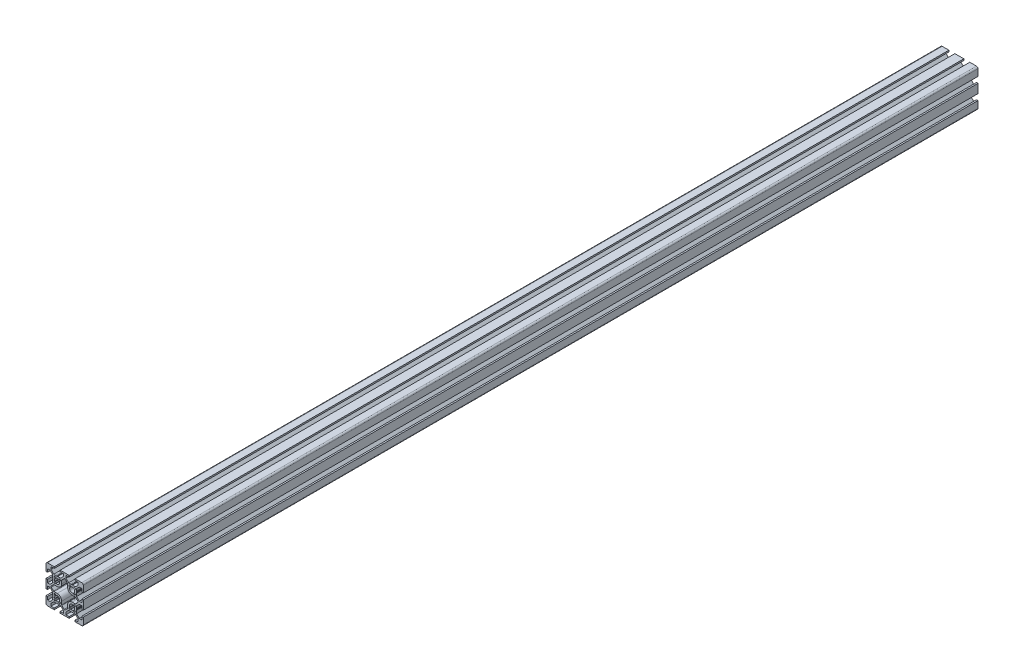
SolidWorks part; units mm, degrees
ref_plane "Front Plane" through (0, 0, 0) normal (0, 0, 1) x (1, 0, 0)
ref_plane "Top Plane" through (0, 0, 0) normal (0, 1, 0) x (1, 0, 0)
ref_plane "Right Plane" through (0, 0, 0) normal (1, 0, 0) x (0, 0, -1)
ref_plane "Plane1" through (0, 0, 0) normal (0, 0, 1) x (1, 0, 0)
sketch "Sketch1" plane through (0, 0, 0) normal (0, 0, 1) x (1, 0, 0)
  line L0 (-25, 23) -> (-25, 14)
  line L1 (-25, 14) -> (-23, 14)
  line L2 (-23, 14) -> (-23, 18.25)
  line L3 (-23, 18.25) -> (-19.6642, 18.25)
  line L4 (-19.6642, 18.25) -> (-16, 14.5858)
  line L5 (-16, 14.5858) -> (-16, 10.6536)
  line L6 (-15.933, 10.4036) -> (-15.7, 10)
  line L7 (-15.7, 10) -> (-15.933, 9.5964)
  line L8 (-15.933, 9.0964) -> (-15.751, 8.7811)
  line L9 (-15.751, 8.7811) -> (-16, 7.5)
  line L10 (-16, 7.5) -> (-16, 5.4142)
  line L11 (-16, 5.4142) -> (-19.6642, 1.75)
  line L12 (-19.6642, 1.75) -> (-23, 1.75)
  line L13 (-23, 1.75) -> (-23, 6)
  line L14 (-23, 6) -> (-25, 6)
  line L15 (-25, 6) -> (-25, -6)
  line L16 (-25, -6) -> (-23, -6)
  line L17 (-23, -6) -> (-23, -1.75)
  line L18 (-23, -1.75) -> (-19.6642, -1.75)
  line L19 (-19.6642, -1.75) -> (-16, -5.4142)
  line L20 (-16, -5.4142) -> (-16, -9.3464)
  line L21 (-15.933, -9.5964) -> (-15.7, -10)
  line L22 (-15.7, -10) -> (-15.933, -10.4036)
  line L23 (-15.933, -10.9036) -> (-15.751, -11.2189)
  line L24 (-15.751, -11.2189) -> (-16, -12.5)
  line L25 (-16, -12.5) -> (-16, -14.5858)
  line L26 (-16, -14.5858) -> (-19.6642, -18.25)
  line L27 (-19.6642, -18.25) -> (-23, -18.25)
  line L28 (-23, -18.25) -> (-23, -14)
  line L29 (-23, -14) -> (-25, -14)
  line L30 (-25, -14) -> (-25, -23)
  line L31 (-23, -25) -> (-14, -25)
  line L32 (-14, -25) -> (-14, -23)
  line L33 (-14, -23) -> (-18.25, -23)
  line L34 (-18.25, -23) -> (-18.25, -19.6642)
  line L35 (-18.25, -19.6642) -> (-14.5858, -16)
  line L36 (-14.5858, -16) -> (-10.6536, -16)
  line L37 (-10.4036, -15.933) -> (-10, -15.7)
  line L38 (-10, -15.7) -> (-9.5964, -15.933)
  line L39 (-9.0964, -15.933) -> (-8.7811, -15.751)
  line L40 (-8.7811, -15.751) -> (-7.5, -16)
  line L41 (-7.5, -16) -> (-5.4142, -16)
  line L42 (-5.4142, -16) -> (-1.75, -19.6642)
  line L43 (-1.75, -19.6642) -> (-1.75, -23)
  line L44 (-1.75, -23) -> (-6, -23)
  line L45 (-6, -23) -> (-6, -25)
  line L46 (-6, -25) -> (6, -25)
  line L47 (6, -25) -> (6, -23)
  line L48 (6, -23) -> (1.75, -23)
  line L49 (1.75, -23) -> (1.75, -19.6642)
  line L50 (1.75, -19.6642) -> (5.4142, -16)
  line L51 (5.4142, -16) -> (9.3464, -16)
  line L52 (9.5964, -15.933) -> (10, -15.7)
  line L53 (10, -15.7) -> (10.4036, -15.933)
  line L54 (10.9036, -15.933) -> (11.2189, -15.751)
  line L55 (11.2189, -15.751) -> (12.5, -16)
  line L56 (12.5, -16) -> (14.5858, -16)
  line L57 (14.5858, -16) -> (18.25, -19.6642)
  line L58 (18.25, -19.6642) -> (18.25, -23)
  line L59 (18.25, -23) -> (14, -23)
  line L60 (14, -23) -> (14, -25)
  line L61 (14, -25) -> (23, -25)
  line L62 (25, -23) -> (25, -14)
  line L63 (25, -14) -> (23, -14)
  line L64 (23, -14) -> (23, -18.25)
  line L65 (23, -18.25) -> (19.6642, -18.25)
  line L66 (19.6642, -18.25) -> (16, -14.5858)
  line L67 (16, -14.5858) -> (16, -10.6536)
  line L68 (15.933, -10.4036) -> (15.7, -10)
  line L69 (15.7, -10) -> (15.933, -9.5964)
  line L70 (15.933, -9.0964) -> (15.751, -8.7811)
  line L71 (15.751, -8.7811) -> (16, -7.5)
  line L72 (16, -7.5) -> (16, -5.4142)
  line L73 (16, -5.4142) -> (19.6642, -1.75)
  line L74 (19.6642, -1.75) -> (23, -1.75)
  line L75 (23, -1.75) -> (23, -6)
  line L76 (23, -6) -> (25, -6)
  line L77 (25, -6) -> (25, 6)
  line L78 (25, 6) -> (23, 6)
  line L79 (23, 6) -> (23, 1.75)
  line L80 (23, 1.75) -> (19.6642, 1.75)
  line L81 (19.6642, 1.75) -> (16, 5.4142)
  line L82 (16, 5.4142) -> (16, 9.3464)
  line L83 (15.933, 9.5964) -> (15.7, 10)
  line L84 (15.7, 10) -> (15.933, 10.4036)
  line L85 (15.933, 10.9036) -> (15.751, 11.2189)
  line L86 (15.751, 11.2189) -> (16, 12.5)
  line L87 (16, 12.5) -> (16, 14.5858)
  line L88 (16, 14.5858) -> (19.6642, 18.25)
  line L89 (19.6642, 18.25) -> (23, 18.25)
  line L90 (23, 18.25) -> (23, 14)
  line L91 (23, 14) -> (25, 14)
  line L92 (25, 14) -> (25, 23)
  line L93 (23, 25) -> (14, 25)
  line L94 (14, 25) -> (14, 23)
  line L95 (14, 23) -> (18.25, 23)
  line L96 (18.25, 23) -> (18.25, 19.6642)
  line L97 (18.25, 19.6642) -> (14.5858, 16)
  line L98 (14.5858, 16) -> (10.6536, 16)
  line L99 (10.4036, 15.933) -> (10, 15.7)
  line L100 (10, 15.7) -> (9.5964, 15.933)
  line L101 (9.0964, 15.933) -> (8.7811, 15.751)
  line L102 (8.7811, 15.751) -> (7.5, 16)
  line L103 (7.5, 16) -> (5.4142, 16)
  line L104 (5.4142, 16) -> (1.75, 19.6642)
  line L105 (1.75, 19.6642) -> (1.75, 23)
  line L106 (1.75, 23) -> (6, 23)
  line L107 (6, 23) -> (6, 25)
  line L108 (6, 25) -> (-6, 25)
  line L109 (-6, 25) -> (-6, 23)
  line L110 (-6, 23) -> (-1.75, 23)
  line L111 (-1.75, 23) -> (-1.75, 19.6642)
  line L112 (-1.75, 19.6642) -> (-5.4142, 16)
  line L113 (-5.4142, 16) -> (-9.3464, 16)
  line L114 (-9.5964, 15.933) -> (-10, 15.7)
  line L115 (-10, 15.7) -> (-10.4036, 15.933)
  line L116 (-10.9036, 15.933) -> (-11.2189, 15.751)
  line L117 (-11.2189, 15.751) -> (-12.5, 16)
  line L118 (-12.5, 16) -> (-14.5858, 16)
  line L119 (-14.5858, 16) -> (-18.25, 19.6642)
  line L120 (-18.25, 19.6642) -> (-18.25, 23)
  line L121 (-18.25, 23) -> (-14, 23)
  line L122 (-14, 23) -> (-14, 25)
  line L123 (-14, 25) -> (-23, 25)
  line L124 (-17.8787, -0.7071) -> (-14.8787, -3.7071)
  line L125 (-14.1716, -4) -> (-10, -4)
  line L126 (-4, -10) -> (-4, -14.1716)
  line L127 (-3.7071, -14.8787) -> (-0.7071, -17.8787)
  line L128 (0.7071, -17.8787) -> (3.7071, -14.8787)
  line L129 (4, -14.1716) -> (4, -10)
  line L130 (10, -4) -> (14.1716, -4)
  line L131 (14.8787, -3.7071) -> (17.8787, -0.7071)
  line L132 (17.8787, 0.7071) -> (14.8787, 3.7071)
  line L133 (14.1716, 4) -> (10, 4)
  line L134 (4, 10) -> (4, 14.1716)
  line L135 (3.7071, 14.8787) -> (0.7071, 17.8787)
  line L136 (-0.7071, 17.8787) -> (-3.7071, 14.8787)
  line L137 (-4, 14.1716) -> (-4, 10)
  line L138 (-10, 4) -> (-14.1716, 4)
  line L139 (-14.8787, 3.7071) -> (-17.8787, 0.7071)
  arc A0 (-16, 10.6536) -> (-15.933, 10.4036) centre (-15.5, 10.6536) ccw
  arc A1 (-15.933, 9.5964) -> (-15.933, 9.0964) centre (-15.5, 9.3464) ccw
  arc A2 (-16, -9.3464) -> (-15.933, -9.5964) centre (-15.5, -9.3464) ccw
  arc A3 (-15.933, -10.4036) -> (-15.933, -10.9036) centre (-15.5, -10.6536) ccw
  arc A4 (-25, -23) -> (-23, -25) centre (-23, -23) ccw
  arc A5 (-10.6536, -16) -> (-10.4036, -15.933) centre (-10.6536, -15.5) ccw
  arc A6 (-9.5964, -15.933) -> (-9.0964, -15.933) centre (-9.3464, -15.5) ccw
  arc A7 (9.3464, -16) -> (9.5964, -15.933) centre (9.3464, -15.5) ccw
  arc A8 (10.4036, -15.933) -> (10.9036, -15.933) centre (10.6536, -15.5) ccw
  arc A9 (23, -25) -> (25, -23) centre (23, -23) ccw
  arc A10 (16, -10.6536) -> (15.933, -10.4036) centre (15.5, -10.6536) ccw
  arc A11 (15.933, -9.5964) -> (15.933, -9.0964) centre (15.5, -9.3464) ccw
  arc A12 (16, 9.3464) -> (15.933, 9.5964) centre (15.5, 9.3464) ccw
  arc A13 (15.933, 10.4036) -> (15.933, 10.9036) centre (15.5, 10.6536) ccw
  arc A14 (25, 23) -> (23, 25) centre (23, 23) ccw
  arc A15 (10.6536, 16) -> (10.4036, 15.933) centre (10.6536, 15.5) ccw
  arc A16 (9.5964, 15.933) -> (9.0964, 15.933) centre (9.3464, 15.5) ccw
  arc A17 (-9.3464, 16) -> (-9.5964, 15.933) centre (-9.3464, 15.5) ccw
  arc A18 (-10.4036, 15.933) -> (-10.9036, 15.933) centre (-10.6536, 15.5) ccw
  arc A19 (-23, 25) -> (-25, 23) centre (-23, 23) ccw
  arc A20 (-17.8787, 0.7071) -> (-17.8787, -0.7071) centre (-17.1716, 0) ccw
  arc A21 (-14.8787, -3.7071) -> (-14.1716, -4) centre (-14.1716, -3) ccw
  arc A22 (-10, -4) -> (-4, -10) centre (-10, -10) cw
  arc A23 (-4, -14.1716) -> (-3.7071, -14.8787) centre (-3, -14.1716) ccw
  arc A24 (-0.7071, -17.8787) -> (0.7071, -17.8787) centre (0, -17.1716) ccw
  arc A25 (3.7071, -14.8787) -> (4, -14.1716) centre (3, -14.1716) ccw
  arc A26 (4, -10) -> (10, -4) centre (10, -10) cw
  arc A27 (14.1716, -4) -> (14.8787, -3.7071) centre (14.1716, -3) ccw
  arc A28 (17.8787, -0.7071) -> (17.8787, 0.7071) centre (17.1716, 0) ccw
  arc A29 (14.8787, 3.7071) -> (14.1716, 4) centre (14.1716, 3) ccw
  arc A30 (10, 4) -> (4, 10) centre (10, 10) cw
  arc A31 (4, 14.1716) -> (3.7071, 14.8787) centre (3, 14.1716) ccw
  arc A32 (0.7071, 17.8787) -> (-0.7071, 17.8787) centre (0, 17.1716) ccw
  arc A33 (-3.7071, 14.8787) -> (-4, 14.1716) centre (-3, 14.1716) ccw
  arc A34 (-4, 10) -> (-10, 4) centre (-10, 10) cw
  arc A35 (-14.1716, 4) -> (-14.8787, 3.7071) centre (-14.1716, 3) ccw
extrude "Boss-Extrude1" add sketch "Sketch1" against normal blind 1200
ref_plane "Plane2" through (0, 0, 0) normal (0, 0, 1) x (1, 0, 0)
sketch "Sketch2" plane through (0, 0, 0) normal (0, 0, 1) x (1, 0, 0)
  line L0 (-14.2426, 12.8284) -> (-13.2051, 11.7909)
  line L1 (-13.2051, 8.2091) -> (-14.2426, 7.1716)
  line L2 (-14.2426, 6.4645) -> (-13.5355, 5.7574)
  line L3 (-12.8284, 5.7574) -> (-11.7909, 6.7949)
  line L4 (-6.7949, 11.7909) -> (-5.7574, 12.8284)
  line L5 (-5.7574, 13.5355) -> (-6.4645, 14.2426)
  line L6 (-7.1716, 14.2426) -> (-8.2091, 13.2051)
  line L7 (-11.7909, 13.2051) -> (-12.8284, 14.2426)
  line L8 (-13.5355, 14.2426) -> (-14.2426, 13.5355)
  arc A0 (-14.2426, 13.5355) -> (-14.2426, 12.8284) centre (-13.8891, 13.182) ccw
  arc A1 (-13.2051, 11.7909) -> (-13.1208, 11.3493) centre (-13.4879, 11.508) cw
  arc A2 (-13.1208, 11.3493) -> (-13.1208, 8.6507) centre (-10, 10) ccw
  arc A3 (-13.1208, 8.6507) -> (-13.2051, 8.2091) centre (-13.4879, 8.492) cw
  arc A4 (-14.2426, 7.1716) -> (-14.2426, 6.4645) centre (-13.8891, 6.818) ccw
  arc A5 (-13.5355, 5.7574) -> (-12.8284, 5.7574) centre (-13.182, 6.1109) ccw
  arc A6 (-11.7909, 6.7949) -> (-11.3493, 6.8792) centre (-11.508, 6.5121) cw
  arc A7 (-11.3493, 6.8792) -> (-6.8792, 11.3493) centre (-10, 10) ccw
  arc A8 (-6.8792, 11.3493) -> (-6.7949, 11.7909) centre (-6.5121, 11.508) cw
  arc A9 (-5.7574, 12.8284) -> (-5.7574, 13.5355) centre (-6.1109, 13.182) ccw
  arc A10 (-6.4645, 14.2426) -> (-7.1716, 14.2426) centre (-6.818, 13.8891) ccw
  arc A11 (-8.2091, 13.2051) -> (-8.6507, 13.1208) centre (-8.492, 13.4879) cw
  arc A12 (-8.6507, 13.1208) -> (-11.3493, 13.1208) centre (-10, 10) ccw
  arc A13 (-11.3493, 13.1208) -> (-11.7909, 13.2051) centre (-11.508, 13.4879) cw
  arc A14 (-12.8284, 14.2426) -> (-13.5355, 14.2426) centre (-13.182, 13.8891) ccw
extrude "Cut-Extrude1" cut sketch "Sketch2" against normal through all
ref_plane "Plane3" through (0, 0, 0) normal (0, 0, 1) x (1, 0, 0)
sketch "Sketch3" plane through (0, 0, 0) normal (0, 0, 1) x (1, 0, 0)
  line L0 (-12.8284, -14.2426) -> (-11.7909, -13.2051)
  line L1 (-8.2091, -13.2051) -> (-7.1716, -14.2426)
  line L2 (-6.4645, -14.2426) -> (-5.7574, -13.5355)
  line L3 (-5.7574, -12.8284) -> (-6.7949, -11.7909)
  line L4 (-11.7909, -6.7949) -> (-12.8284, -5.7574)
  line L5 (-13.5355, -5.7574) -> (-14.2426, -6.4645)
  line L6 (-14.2426, -7.1716) -> (-13.2051, -8.2091)
  line L7 (-13.2051, -11.7909) -> (-14.2426, -12.8284)
  line L8 (-14.2426, -13.5355) -> (-13.5355, -14.2426)
  arc A0 (-13.5355, -14.2426) -> (-12.8284, -14.2426) centre (-13.182, -13.8891) ccw
  arc A1 (-11.7909, -13.2051) -> (-11.3493, -13.1208) centre (-11.508, -13.4879) cw
  arc A2 (-11.3493, -13.1208) -> (-8.6507, -13.1208) centre (-10, -10) ccw
  arc A3 (-8.6507, -13.1208) -> (-8.2091, -13.2051) centre (-8.492, -13.4879) cw
  arc A4 (-7.1716, -14.2426) -> (-6.4645, -14.2426) centre (-6.818, -13.8891) ccw
  arc A5 (-5.7574, -13.5355) -> (-5.7574, -12.8284) centre (-6.1109, -13.182) ccw
  arc A6 (-6.7949, -11.7909) -> (-6.8792, -11.3493) centre (-6.5121, -11.508) cw
  arc A7 (-6.8792, -11.3493) -> (-11.3493, -6.8792) centre (-10, -10) ccw
  arc A8 (-11.3493, -6.8792) -> (-11.7909, -6.7949) centre (-11.508, -6.5121) cw
  arc A9 (-12.8284, -5.7574) -> (-13.5355, -5.7574) centre (-13.182, -6.1109) ccw
  arc A10 (-14.2426, -6.4645) -> (-14.2426, -7.1716) centre (-13.8891, -6.818) ccw
  arc A11 (-13.2051, -8.2091) -> (-13.1208, -8.6507) centre (-13.4879, -8.492) cw
  arc A12 (-13.1208, -8.6507) -> (-13.1208, -11.3493) centre (-10, -10) ccw
  arc A13 (-13.1208, -11.3493) -> (-13.2051, -11.7909) centre (-13.4879, -11.508) cw
  arc A14 (-14.2426, -12.8284) -> (-14.2426, -13.5355) centre (-13.8891, -13.182) ccw
extrude "Cut-Extrude2" cut sketch "Sketch3" against normal through all
ref_plane "Plane4" through (0, 0, 0) normal (0, 0, 1) x (1, 0, 0)
sketch "Sketch4" plane through (0, 0, 0) normal (0, 0, 1) x (1, 0, 0)
  line L0 (14.2426, -12.8284) -> (13.2051, -11.7909)
  line L1 (13.2051, -8.2091) -> (14.2426, -7.1716)
  line L2 (14.2426, -6.4645) -> (13.5355, -5.7574)
  line L3 (12.8284, -5.7574) -> (11.7909, -6.7949)
  line L4 (6.7949, -11.7909) -> (5.7574, -12.8284)
  line L5 (5.7574, -13.5355) -> (6.4645, -14.2426)
  line L6 (7.1716, -14.2426) -> (8.2091, -13.2051)
  line L7 (11.7909, -13.2051) -> (12.8284, -14.2426)
  line L8 (13.5355, -14.2426) -> (14.2426, -13.5355)
  arc A0 (14.2426, -13.5355) -> (14.2426, -12.8284) centre (13.8891, -13.182) ccw
  arc A1 (13.2051, -11.7909) -> (13.1208, -11.3493) centre (13.4879, -11.508) cw
  arc A2 (13.1208, -11.3493) -> (13.1208, -8.6507) centre (10, -10) ccw
  arc A3 (13.1208, -8.6507) -> (13.2051, -8.2091) centre (13.4879, -8.492) cw
  arc A4 (14.2426, -7.1716) -> (14.2426, -6.4645) centre (13.8891, -6.818) ccw
  arc A5 (13.5355, -5.7574) -> (12.8284, -5.7574) centre (13.182, -6.1109) ccw
  arc A6 (11.7909, -6.7949) -> (11.3493, -6.8792) centre (11.508, -6.5121) cw
  arc A7 (11.3493, -6.8792) -> (6.8792, -11.3493) centre (10, -10) ccw
  arc A8 (6.8792, -11.3493) -> (6.7949, -11.7909) centre (6.5121, -11.508) cw
  arc A9 (5.7574, -12.8284) -> (5.7574, -13.5355) centre (6.1109, -13.182) ccw
  arc A10 (6.4645, -14.2426) -> (7.1716, -14.2426) centre (6.818, -13.8891) ccw
  arc A11 (8.2091, -13.2051) -> (8.6507, -13.1208) centre (8.492, -13.4879) cw
  arc A12 (8.6507, -13.1208) -> (11.3493, -13.1208) centre (10, -10) ccw
  arc A13 (11.3493, -13.1208) -> (11.7909, -13.2051) centre (11.508, -13.4879) cw
  arc A14 (12.8284, -14.2426) -> (13.5355, -14.2426) centre (13.182, -13.8891) ccw
extrude "Cut-Extrude3" cut sketch "Sketch4" against normal through all
ref_plane "Plane5" through (0, 0, 0) normal (0, 0, 1) x (1, 0, 0)
sketch "Sketch5" plane through (0, 0, 0) normal (0, 0, 1) x (1, 0, 0)
  line L0 (12.8284, 14.2426) -> (11.7909, 13.2051)
  line L1 (8.2091, 13.2051) -> (7.1716, 14.2426)
  line L2 (6.4645, 14.2426) -> (5.7574, 13.5355)
  line L3 (5.7574, 12.8284) -> (6.7949, 11.7909)
  line L4 (11.7909, 6.7949) -> (12.8284, 5.7574)
  line L5 (13.5355, 5.7574) -> (14.2426, 6.4645)
  line L6 (14.2426, 7.1716) -> (13.2051, 8.2091)
  line L7 (13.2051, 11.7909) -> (14.2426, 12.8284)
  line L8 (14.2426, 13.5355) -> (13.5355, 14.2426)
  arc A0 (13.5355, 14.2426) -> (12.8284, 14.2426) centre (13.182, 13.8891) ccw
  arc A1 (11.7909, 13.2051) -> (11.3493, 13.1208) centre (11.508, 13.4879) cw
  arc A2 (11.3493, 13.1208) -> (8.6507, 13.1208) centre (10, 10) ccw
  arc A3 (8.6507, 13.1208) -> (8.2091, 13.2051) centre (8.492, 13.4879) cw
  arc A4 (7.1716, 14.2426) -> (6.4645, 14.2426) centre (6.818, 13.8891) ccw
  arc A5 (5.7574, 13.5355) -> (5.7574, 12.8284) centre (6.1109, 13.182) ccw
  arc A6 (6.7949, 11.7909) -> (6.8792, 11.3493) centre (6.5121, 11.508) cw
  arc A7 (6.8792, 11.3493) -> (11.3493, 6.8792) centre (10, 10) ccw
  arc A8 (11.3493, 6.8792) -> (11.7909, 6.7949) centre (11.508, 6.5121) cw
  arc A9 (12.8284, 5.7574) -> (13.5355, 5.7574) centre (13.182, 6.1109) ccw
  arc A10 (14.2426, 6.4645) -> (14.2426, 7.1716) centre (13.8891, 6.818) ccw
  arc A11 (13.2051, 8.2091) -> (13.1208, 8.6507) centre (13.4879, 8.492) cw
  arc A12 (13.1208, 8.6507) -> (13.1208, 11.3493) centre (10, 10) ccw
  arc A13 (13.1208, 11.3493) -> (13.2051, 11.7909) centre (13.4879, 11.508) cw
  arc A14 (14.2426, 12.8284) -> (14.2426, 13.5355) centre (13.8891, 13.182) ccw
extrude "Cut-Extrude4" cut sketch "Sketch5" against normal through all
